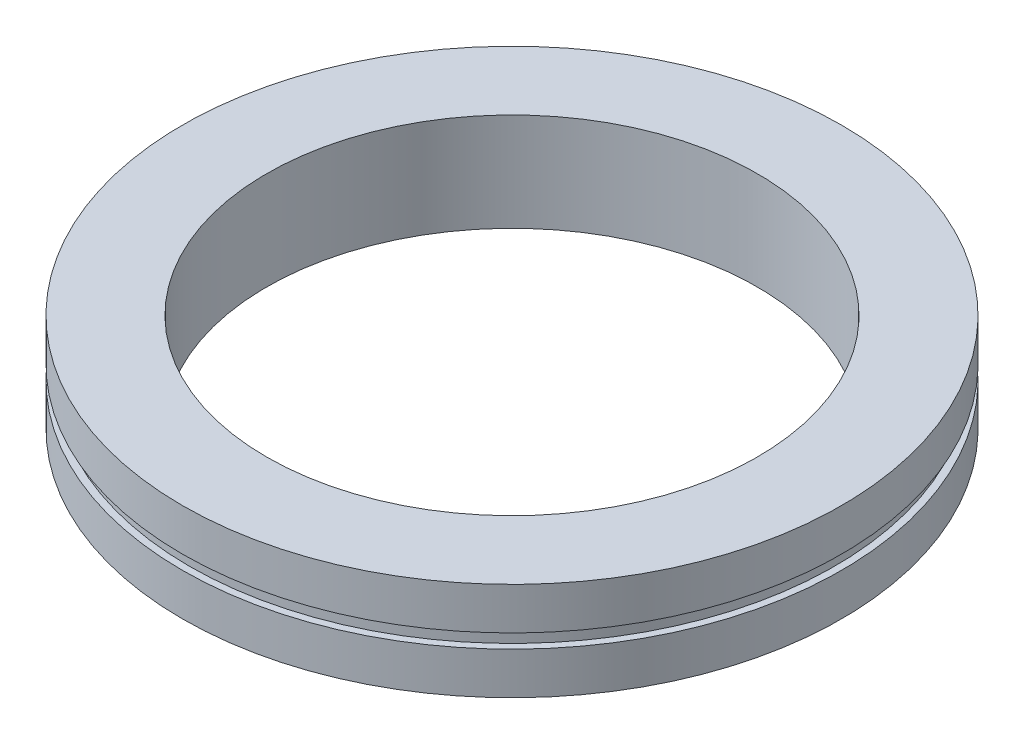
SolidWorks part; units mm, degrees
material "合金钢"
ref_plane "前视基准面" through (0, 0, 0) normal (0, 0, 1) x (1, 0, 0)
ref_plane "上视基准面" through (0, 0, 0) normal (0, 1, 0) x (1, 0, 0)
ref_plane "右视基准面" through (0, 0, 0) normal (1, 0, 0) x (0, 0, -1)
sketch "草图1" plane through (0, 0, 0) normal (0, 1, 0) x (1, 0, 0)
  circle A0 centre (0, 0) radius 17.5
  circle A1 centre (0, 0) radius 23.5
  dimension "D1" = 35
  dimension "D2" = 47
extrude "凸台-拉伸1" add sketch "草图1" along normal blind 7
sketch "草图2" plane through (0, 0, 0) normal (0, 0, 1) x (1, 0, 0)
  line L0 (0, 7) -> (0, 0) construction
  line L1 (17.5, 7) -> (-17.5, 7) construction
  line L2 (0, 3.5) -> (23.5, 3.5) construction
  line L3 (23.5, 0) -> (23.5, 7) construction
  line L4 (23.5, 3) -> (23, 3)
  line L5 (23.5, 4) -> (23, 4)
  line L6 (23.5, 4) -> (23.5, 3)
  line L8 (23, 4) -> (23, 3)
  point P14 (23, 3.5)
  dimension "D1" = 1
  dimension "D2" = 0.5
revolve "切除-旋转1" cut sketch "草图2" angle 360 about L0
